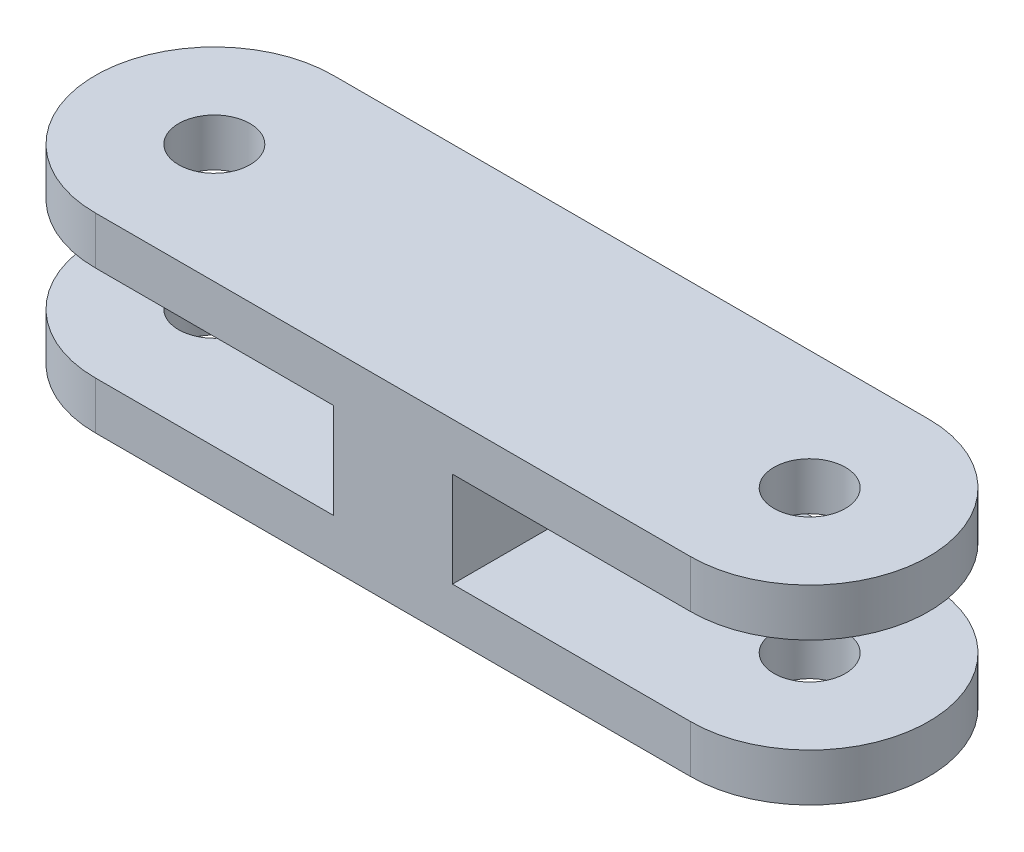
SolidWorks part; units mm, degrees
ref_plane "前视基准面" through (0, 0, 0) normal (0, 0, 1) x (1, 0, 0)
ref_plane "上视基准面" through (0, 0, 0) normal (0, 1, 0) x (1, 0, 0)
ref_plane "右视基准面" through (0, 0, 0) normal (1, 0, 0) x (0, 0, -1)
other "Configuration Table"
sketch "草图1" plane through (0, 0, 0) normal (0, 1, 0) x (1, 0, 0)
  line L0 (-125, 0) -> (125, 0) construction
  line L1 (-125, 50) -> (125, 50)
  line L2 (-125, -50) -> (125, -50)
  arc A0 (-125, 50) -> (-125, -50) centre (-125, 0) ccw
  arc A1 (125, -50) -> (125, 50) centre (125, 0) ccw
  circle A2 centre (-125, 0) radius 15
  circle A3 centre (125, 0) radius 15
  point P2 (0, 0)
  dimension "D5" = 50
  dimension "D6" = 30
  dimension "D7" = 30
  dimension "D1" = 0
  dimension "D2" = 0
  dimension "D3" = 0
  dimension "D4" = 250
extrude "凸台-拉伸1" add sketch "草图1" along normal blind 80
sketch "草图2" plane through (0, 0, 50) normal (0, 0, 1) x (1, 0, 0)
  line L0 (-125, 80) -> (-125, 0) construction
  line L1 (-225, 60) -> (-25, 60)
  line L2 (-225, 60) -> (-225, 20)
  line L3 (-225, 20) -> (-25, 20)
  line L4 (-25, 60) -> (-25, 20)
  line L5 (-125, 80) -> (125, 80) construction
  line L6 (-125, 0) -> (125, 0) construction
  line L7 (25, 60) -> (225, 60)
  line L8 (25, 60) -> (25, 20)
  line L9 (25, 20) -> (225, 20)
  line L10 (225, 60) -> (225, 20)
  dimension "D1" = 100
  dimension "D2" = 20
  dimension "D3" = 20
  dimension "D4" = 200
  dimension "D5" = 50
  dimension "D6" = 200
  dimension "D7" = 40
  dimension "D8" = 20
extrude "切除-拉伸1" cut sketch "草图2" against normal blind 125
